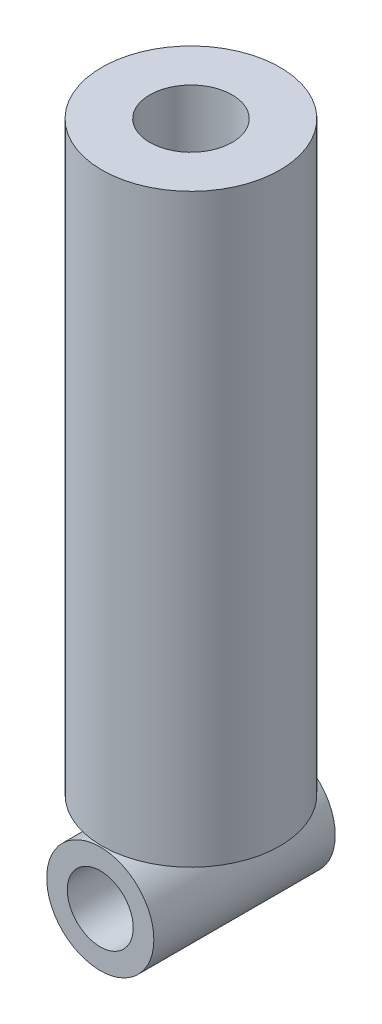
SolidWorks part; units mm, degrees
ref_plane "前视基准面" through (0, 0, 0) normal (0, 0, 1) x (1, 0, 0)
ref_plane "上视基准面" through (0, 0, 0) normal (0, 1, 0) x (1, 0, 0)
ref_plane "右视基准面" through (0, 0, 0) normal (1, 0, 0) x (0, 0, -1)
sketch "草图1" plane through (0, 0, 0) normal (0, 1, 0) x (1, 0, 0)
  circle A0 centre (0, 0) radius 54
  dimension "D1" = 108
extrude "凸台-拉伸1" add sketch "草图1" along normal blind 355
sketch "草图2" plane through (0, 355, 0) normal (0, 1, 0) x (1, 0, 0)
  circle A0 centre (0, 0) radius 25
  dimension "D1" = 50
extrude "切除-拉伸1" cut sketch "草图2" against normal blind 340
sketch "草图3" plane through (0, 0, 0) normal (0, 0, 1) x (1, 0, 0)
  line L0 (0, 0) -> (0, -122.0156) construction
  line L1 (-54, 0) -> (54, 0) construction
  circle A0 centre (0, -32.5) radius 32.5
  circle A1 centre (0, -32.5) radius 20
  dimension "D1" = 65
  dimension "D2" = 40
extrude "凸台-拉伸2" add sketch "草图3" along normal mid plane 110 separate body
ref_plane "基准面1" through (0, -32.5, 0) normal (0, 1, 0) x (1, 0, 0)
